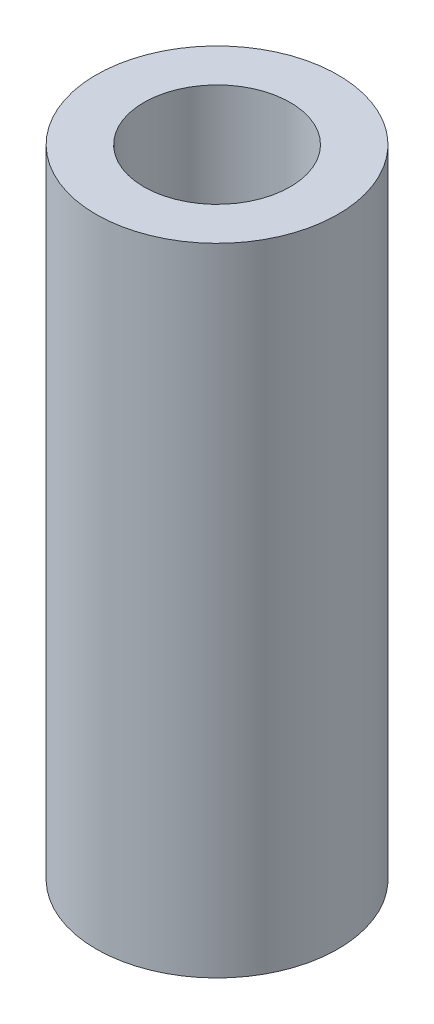
SolidWorks part; units mm, degrees
ref_plane "Front Plane" through (0, 0, 0) normal (0, 0, 1) x (1, 0, 0)
ref_plane "Top Plane" through (0, 0, 0) normal (0, 1, 0) x (1, 0, 0)
ref_plane "Right Plane" through (0, 0, 0) normal (1, 0, 0) x (0, 0, -1)
sketch "Sketch1" plane through (0, 0, 0) normal (0, 1, 0) x (1, 0, 0)
  circle A0 centre (0, 0) radius 2.3
  circle A1 centre (0, 0) radius 3.8
  dimension "D1" = 4.6
  dimension "D2" = 7.6
extrude "Boss-Extrude1" add sketch "Sketch1" along normal blind 20
